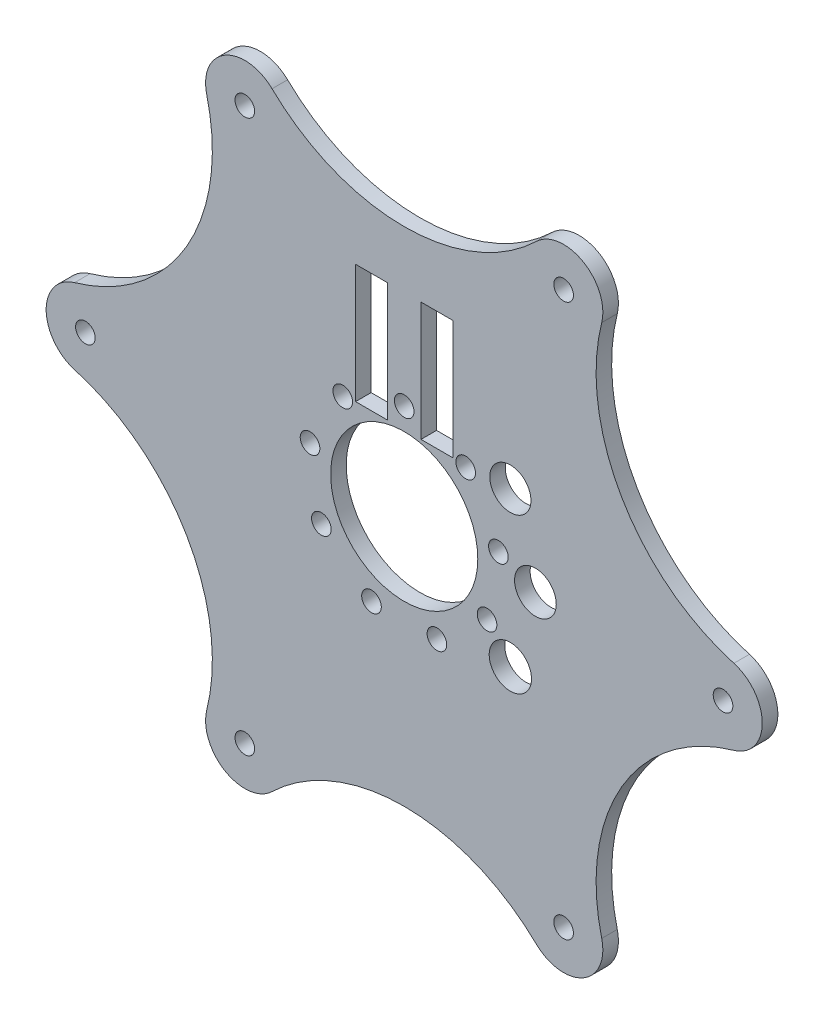
SolidWorks part; units mm, degrees
ref_plane "Front Plane" through (0, 0, 0) normal (0, 0, 1) x (1, 0, 0)
ref_plane "Top Plane" through (0, 0, 0) normal (0, 1, 0) x (1, 0, 0)
ref_plane "Right Plane" through (0, 0, 0) normal (1, 0, 0) x (0, 0, -1)
sketch "Sketch2" plane through (0, 0, 0) normal (0, 0, 1) x (1, 0, 0)
  line L0 (0, 0) -> (0, 153.4686) construction
  line L1 (0, 0) -> (169.2389, 0) construction
  line L2 (65, 112.5833) -> (0, 0) construction
  line L3 (-9.3635, 77.648) -> (-17.3141, 77.648) construction
  line L4 (-9.3635, 77.648) -> (-17.3141, 77.648) construction
  line L5 (-6.8388, 79.148) -> (-6.8388, 30.648)
  line L6 (-6.8388, 30.648) -> (-19.8388, 30.648)
  line L7 (-19.8388, 30.648) -> (-19.8388, 79.148)
  line L8 (-19.8388, 79.148) -> (-6.8388, 79.148)
  line L9 (-13.3388, 79.148) -> (-13.3388, 77.648) construction
  line L10 (-8.3388, 53.048) -> (-8.3388, 70.348) construction
  line L11 (-8.3388, 53.048) -> (-8.3388, 70.348) construction
  line L12 (-13.3388, 30.648) -> (-13.3388, 31.648) construction
  line L13 (6.8388, 30.648) -> (19.8388, 30.648)
  line L14 (6.8388, 79.148) -> (6.8388, 30.648)
  line L15 (19.8388, 30.648) -> (19.8388, 79.148)
  line L16 (19.8388, 79.148) -> (6.8388, 79.148)
  line L17 (0, 0) -> (157.3802, 90.8635) construction
  circle A0 centre (65, 112.5833) radius 4
  circle A6 centre (130, 0) radius 4
  circle A7 centre (65, -112.5833) radius 4
  circle A8 centre (-65, -112.5833) radius 4
  circle A9 centre (-130, 0) radius 4
  circle A10 centre (-65, 112.5833) radius 4
  circle A11 centre (25.0687, 29.8757) radius 4 construction
  circle A12 centre (38.4075, 6.7723) radius 4 construction
  circle A13 centre (33.775, -19.5) radius 4 construction
  circle A14 centre (13.3388, -36.648) radius 4 construction
  circle A15 centre (-13.3388, -36.648) radius 4 construction
  circle A16 centre (-33.775, -19.5) radius 4 construction
  circle A17 centre (-38.4075, 6.7723) radius 4 construction
  circle A18 centre (-25.0687, 29.8757) radius 4 construction
  circle A19 centre (25.0687, 29.8757) radius 4
  circle A20 centre (38.4075, 6.7723) radius 4
  circle A21 centre (33.775, -19.5) radius 4
  circle A22 centre (13.3388, -36.648) radius 4
  circle A23 centre (-13.3388, -36.648) radius 4
  circle A24 centre (-33.775, -19.5) radius 4
  circle A25 centre (-38.4075, 6.7723) radius 4
  circle A26 centre (-25.0687, 29.8757) radius 4
  circle A27 centre (-13.3388, 36.648) radius 5 construction
  circle A28 centre (-13.3388, 36.648) radius 5 construction
  circle A29 centre (0, 0) radius 30
  arc A30 (80.5278, 108.7249) -> (53.8946, 124.1016) centre (65, 112.5833) ccw
  arc A31 (88.6391, 51.1758) -> (80.5278, 108.7249) centre (155.8846, 90) cw
  arc A32 (0, 102.3517) -> (53.8946, 124.1016) centre (0, 180) ccw
  arc A33 (88.6391, 51.1758) -> (134.4224, 15.3767) centre (155.8846, 90) ccw
  arc A34 (134.4224, -15.3767) -> (134.4224, 15.3767) centre (130, 0) ccw
  arc A35 (88.6391, -51.1758) -> (134.4224, -15.3767) centre (155.8846, -90) cw
  arc A36 (88.6391, -51.1758) -> (80.5278, -108.7249) centre (155.8846, -90) ccw
  arc A37 (53.8946, -124.1016) -> (80.5278, -108.7249) centre (65, -112.5833) ccw
  arc A38 (0, -102.3517) -> (53.8946, -124.1016) centre (0, -180) cw
  arc A39 (0, -102.3517) -> (-53.8946, -124.1016) centre (0, -180) ccw
  arc A40 (-80.5278, -108.7249) -> (-53.8946, -124.1016) centre (-65, -112.5833) ccw
  arc A41 (-88.6391, -51.1758) -> (-80.5278, -108.7249) centre (-155.8846, -90) cw
  arc A42 (-88.6391, -51.1758) -> (-134.4224, -15.3767) centre (-155.8846, -90) ccw
  arc A43 (-134.4224, 15.3767) -> (-134.4224, -15.3767) centre (-130, 0) ccw
  arc A44 (-88.6391, 51.1758) -> (-134.4224, 15.3767) centre (-155.8846, 90) cw
  arc A45 (-88.6391, 51.1758) -> (-80.5278, 108.7249) centre (-155.8846, 90) ccw
  arc A46 (-53.8946, 124.1016) -> (-80.5278, 108.7249) centre (-65, 112.5833) ccw
  arc A47 (0, 102.3517) -> (-53.8946, 124.1016) centre (0, 180) cw
  circle A48 centre (43.2784, 31.4436) radius 6.402 construction
  circle A49 centre (53.495, 0) radius 6.5058 construction
  circle A50 centre (43.2784, -31.4436) radius 6.6233 construction
  circle A51 centre (43.2784, 31.4436) radius 6.402 construction
  circle A52 centre (53.495, 0) radius 6.5058 construction
  circle A53 centre (43.2784, -31.4436) radius 6.6233 construction
  circle A54 centre (43.2784, -31.4436) radius 8.6233
  circle A55 centre (53.495, 0) radius 8.5058
  circle A56 centre (43.2784, 31.4436) radius 8.402
  circle A57 centre (0, 39) radius 4 construction
  circle A58 centre (0, 39) radius 4
  point P19 (0, 0)
  point P20 (0, 0)
  point P54 (-6.8388, 54.898)
  point P108 (0, 0)
  dimension "D3" = 8
  dimension "D5" = 1.5
  dimension "D8" = 60
  dimension "D10" = 12
  dimension "D2" = 130
  dimension "D1" = 30
  dimension "D6" = 1.5
  dimension "D7" = 1
  dimension "D9" = 30
  dimension "D11" = 180
  dimension "D13" = 2
  dimension "D4" = 6
  dimension "D12" = 6
extrude "Boss-Extrude1" add sketch "Sketch2" along normal blind 6.35
